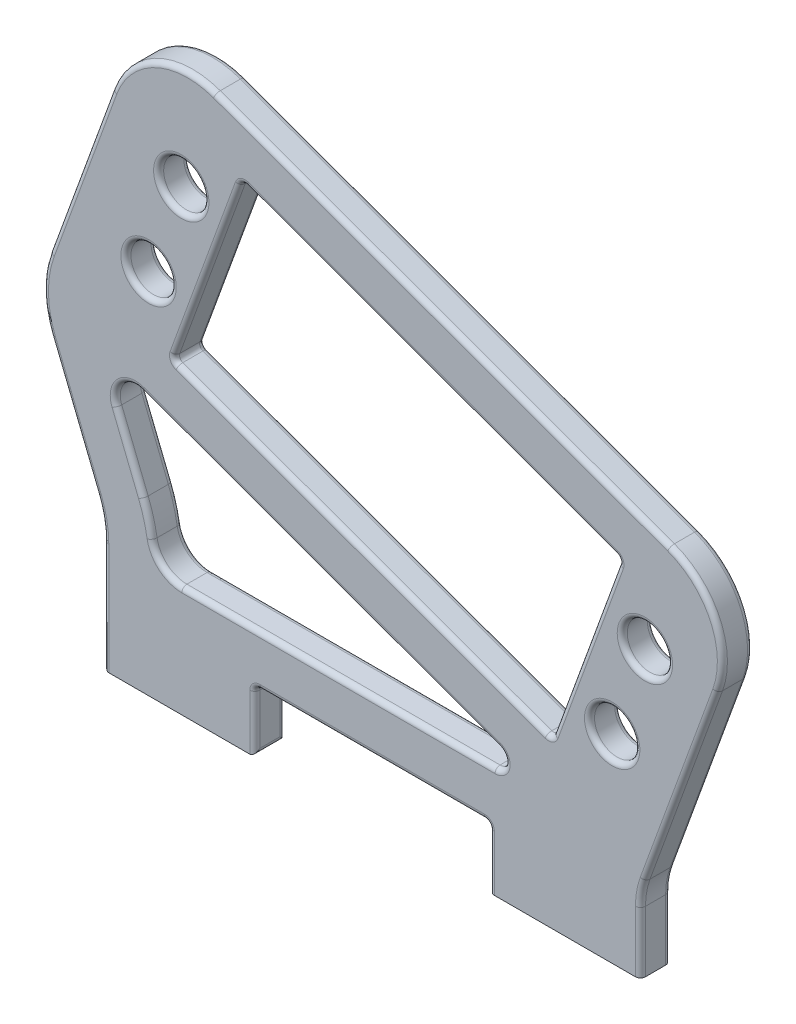
SolidWorks part; units mm, degrees
ref_plane "Front Plane" through (0, 0, 0) normal (0, 0, 1) x (1, 0, 0)
ref_plane "Top Plane" through (0, 0, 0) normal (0, 1, 0) x (1, 0, 0)
ref_plane "Right Plane" through (0, 0, 0) normal (1, 0, 0) x (0, 0, -1)
sketch "Sketch1" plane through (0, 0, 0) normal (0, 0, 1) x (1, 0, 0)
  line L0 (0, 0) -> (15, 0)
  line L1 (15, 0) -> (15, 6)
  line L2 (15, 6) -> (38.3, 6)
  line L3 (38.3, 6) -> (38.3, 0)
  line L4 (38.3, 0) -> (53.3, 0)
  line L5 (53.3, 0) -> (53.3, 7.3867)
  line L6 (6.8829, 30.0233) -> (13.7233, 48.8171)
  line L7 (13.7233, 48.8171) -> (51.311, 35.1363)
  line L8 (0, 0) -> (0, 13)
  line L9 (51.311, 35.1363) -> (44.4706, 16.3425)
  line L10 (44.4706, 16.3425) -> (6.8829, 30.0233)
  line L11 (47.8908, 25.7394) -> (10.3031, 39.4202) construction
  line L12 (53.3, 7.3867) -> (63.696, 35.9494)
  line L13 (63.696, 35.9494) -> (3.5557, 57.8387)
  line L14 (29.0969, 32.5798) -> (32.5171, 41.9767) construction
  line L21 (3.5557, 57.8387) -> (-6.7049, 29.6479)
  line L22 (0, 13) -> (-6.7049, 29.6479)
  circle A0 centre (19.7, 36) radius 2.1 construction
  circle A1 centre (19.7, 36) radius 10 construction
  circle A6 centre (7.6991, 45.4228) radius 2.25
  circle A7 centre (4.4499, 36.4958) radius 2.25
  circle A8 centre (53.744, 28.6638) radius 2.25
  circle A9 centre (50.4948, 19.7368) radius 2.25
  dimension "D5" = 4.2
  dimension "D7" = 20
  dimension "D10" = 40
  dimension "D12" = 20
  dimension "D13" = 64
  dimension "D19" = 4.5
  dimension "D20" = 4.75
  dimension "D21" = 24.5
  dimension "D1" = 15
  dimension "D2" = 6
  dimension "D3" = 23.3
  dimension "D4" = 15
  dimension "D6" = 36
  dimension "D8" = 19.7
  dimension "D9" = 13
  dimension "D11" = 20
  dimension "D22" = 5
  dimension "D23" = 12.64
  dimension "D24" = 30
extrude "Boss-Extrude1" add sketch "Sketch1" along normal blind 3
fillet "Fillet1" radius 8 2 edges at (63.696, 35.9494, 1.5) (3.5557, 57.8387, 1.5)
fillet "Fillet2" radius 10 2 edges at (-6.7049, 29.6479, 1.5) (0, 13, 1.5)
fillet "Fillet3" radius 7.5 1 edges at (53.3, 7.3867, 1.5)
sketch "Sketch2" plane through (0, 0, 3) normal (0, 0, 1) x (1, 0, 0)
  line L20 (3.9139, 16.6657) -> (-0.6353, 27.961)
  line L21 (3.9139, 16.6657) -> (1.2869, 23.1884)
  line L23 (5.1728, 25.3248) -> (42.7605, 11.644)
  line L24 (3.8262, 25.8149) -> (39.2006, 12.9397)
  line L26 (15, 11) -> (38.3, 11)
  line L27 (7.7586, 11) -> (38.8586, 11)
  arc A0 (1.2869, 23.1884) -> (3.8262, 25.8149) centre (3.1421, 23.9356) cw
  arc A1 (4.7988, 13.5103) -> (7.7586, 11) centre (7.7586, 14) ccw
  arc A2 (38.8586, 11) -> (39.2006, 12.9397) centre (38.8586, 12) ccw
  arc A11 (5, 11.0619) -> (3.9139, 16.6657) centre (-10, 11.0619) ccw
  arc A12 (4.7988, 13.5103) -> (3.9139, 16.6657) centre (-10, 11.0619) ccw
  dimension "D4" = 2
  dimension "D5" = 3
  dimension "D6" = 1
  dimension "D1" = 5
  dimension "D2" = 5
  dimension "D3" = 5
extrude "Cut-Extrude1" cut sketch "Sketch2" against normal blind 10
fillet "Fillet4" radius 0.5 66 edges at (38.3, 3, 3) (38.3, 3, 0) (23.3086, 11, 3) (5.8181, 11.7121, 3) (4.4428, 15.1123, 3) (2.6004, 19.927, 3) (1.7042, 25.3257, 3) (21.5134, 19.3773, 3) (21.5134, 19.3773, 0) (1.7042, 25.3257, 0) (2.6004, 19.927, 0) (4.4428, 15.1123, 0) (5.8181, 11.7121, 0) (23.3086, 11, 0) (53.3, 3.0321, 0) (53.4139, 7.3666, 0) (57.3561, 18.5306, 0) (60.6927, 34.549, 0) (33.6258, 46.8941, 0) (4.9561, 54.8355, 0) (-2.2874, 41.7852, 0) (-5.9959, 29.6599, 0) (-2.9986, 20.4454, 0) (-0.1827, 12.9646, 0) (53.3, 3.0321, 3) (53.4139, 7.3666, 3) (57.3561, 18.5306, 3) (60.6927, 34.549, 3) (33.6258, 46.8941, 3) (4.9561, 54.8355, 3) (-2.2874, 41.7852, 3) (-5.9959, 29.6599, 3) (-2.9986, 20.4454, 3) (-0.1827, 12.9646, 3) (26.65, 6, 3) (38.3, 6, 1.5) (26.65, 6, 0) (15, 0, 1.5) (15, 3, 3) (15, 6, 1.5) (15, 3, 0) (25.6767, 23.1829, 3) (25.6767, 23.1829, 0) (6.8829, 30.0233, 1.5) (10.3031, 39.4202, 3) (10.3031, 39.4202, 0) (13.7233, 48.8171, 1.5) (32.5171, 41.9767, 3) (32.5171, 41.9767, 0) (51.311, 35.1363, 1.5) (47.8908, 25.7394, 3) (44.4706, 16.3425, 1.5) (47.8908, 25.7394, 0) (2.1999, 36.4958, 0) (2.1999, 36.4958, 3) (9.9491, 45.4228, 0) (9.9491, 45.4228, 3) (51.494, 28.6638, 0) (51.494, 28.6638, 3) (52.7448, 19.7368, 0) (52.7448, 19.7368, 3) (39.8434, 11.8264, 3) (39.8434, 11.8264, 0) (0, 0, 1.5) (0, 5.5309, 0) (0, 5.5309, 3)
